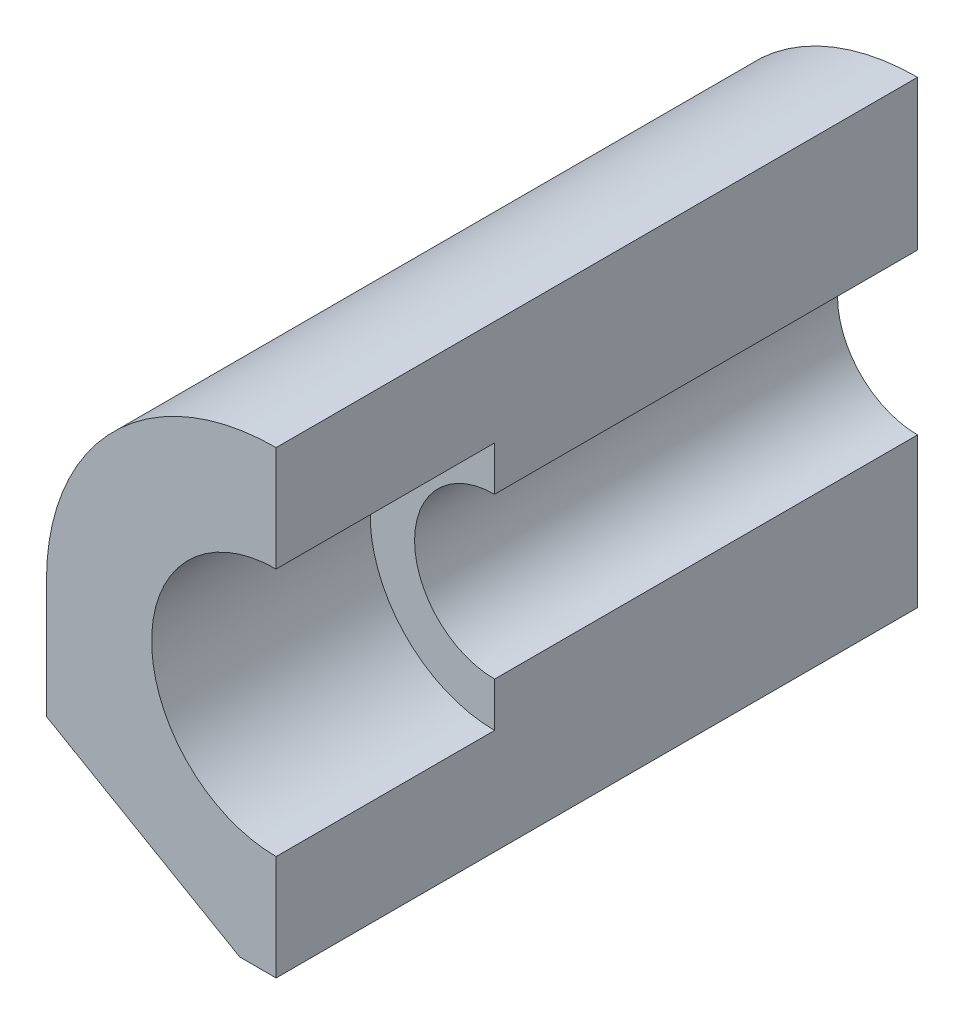
SolidWorks part; units mm, degrees
material "1060 Alloy"
ref_plane "Front Plane" through (0, 0, 0) normal (0, 0, 1) x (1, 0, 0)
ref_plane "Top Plane" through (0, 0, 0) normal (0, 1, 0) x (1, 0, 0)
ref_plane "Right Plane" through (0, 0, 0) normal (1, 0, 0) x (0, 0, -1)
sketch "Sketch2" plane through (0, 0, 0) normal (0, 0, 1) x (1, 0, 0)
  line L0 (0, 0) -> (0, 164)
  line L1 (-82, 82) -> (-82, 39.8372)
  line L2 (-82, 39.8372) -> (-13, 0)
  line L3 (-13, 0) -> (0, 0)
  arc A0 (0, 164) -> (-82, 82) centre (0, 82) ccw
  point P5 (0, 82)
  dimension "D4" = 82
  dimension "D1" = 82
  dimension "D2" = 30
  dimension "D3" = 82
  dimension "D5" = 13
extrude "Boss-Extrude1" add sketch "Sketch2" along normal blind 229
sketch "Sketch3" plane through (0, 0, 229) normal (0, 0, 1) x (1, 0, 0)
  line L0 (0, 0) -> (0, 164) construction
  circle A0 centre (0, 82) radius 44.45
  dimension "D1" = 88.9
extrude "Cut-Extrude1" cut sketch "Sketch3" against normal blind 78
sketch "Sketch4" plane through (0, 0, 151) normal (0, 0, 1) x (1, 0, 0)
  line L0 (0, 37.55) -> (0, 126.45) construction
  circle A0 centre (0, 82) radius 28.575
  dimension "D1" = 57.15
extrude "Cut-Extrude2" cut sketch "Sketch4" against normal through all
ref_plane "Plane1" through (0, 164, 0) normal (0, 1, 0) x (1, 0, 0)
equation "\"A\"= 229mm"
equation "\"B\"= 114mm"
equation "\"C\"= 82mm"
equation "\"D1@Sketch2\"=\"C\""
equation "\"D3@Sketch2\"=\"C\""
equation "\"D4@Sketch2\"=\"C\""
equation "\"D1@Boss-Extrude1\"=\"A\""
equation "\"D1@Sketch7\"=\"B\""
